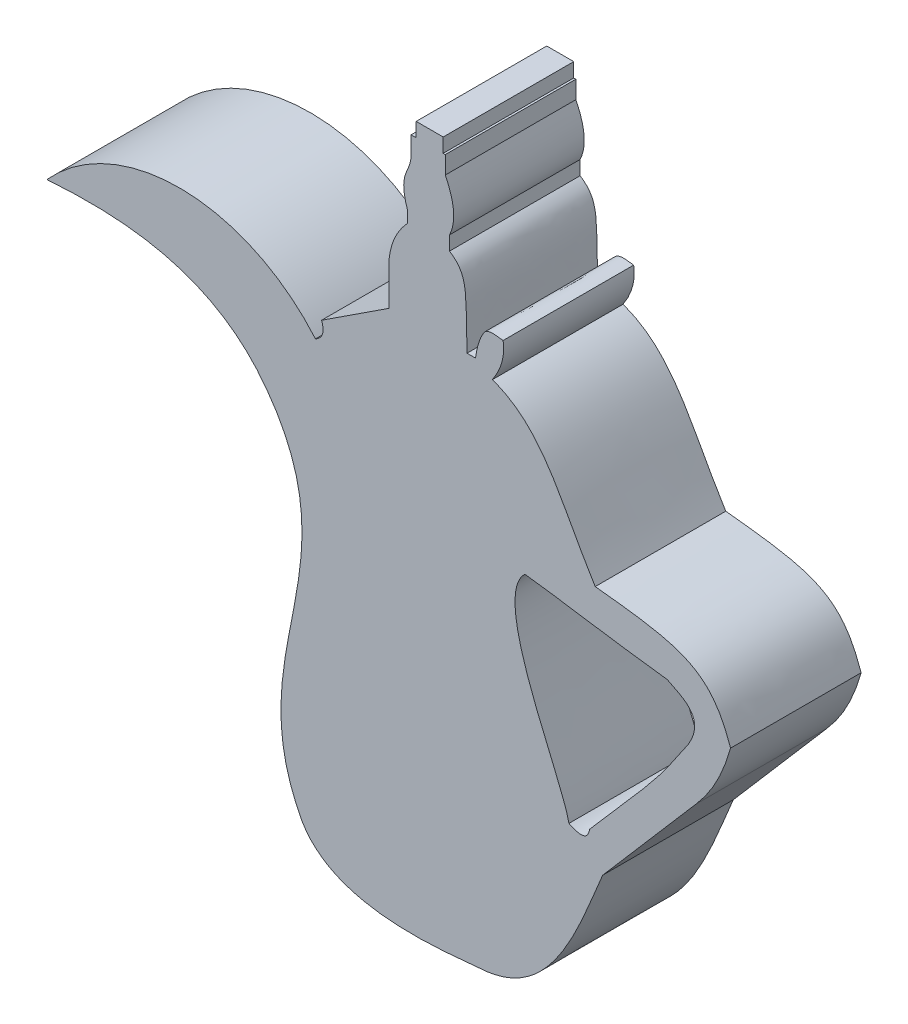
SolidWorks part; units mm, degrees
ref_plane "Front Plane" through (0, 0, 0) normal (0, 0, 1) x (1, 0, 0)
ref_plane "Top Plane" through (0, 0, 0) normal (0, 1, 0) x (1, 0, 0)
ref_plane "Right Plane" through (0, 0, 0) normal (1, 0, 0) x (0, 0, -1)
sketch "Sketch3" plane through (0, 0, 0) normal (0, 0, 1) x (1, 0, 0)
  line L0 (97.4864, 0) -> (97.4864, 192.0589) construction
  line L1 (104, 194) -> (111.2431, 194)
  line L8 (179, 73) -> (154, 44)
  line L9 (78.6407, 135.1556) -> (96.781, 147)
  line L11 (101.7339, 172.1213) -> (101.7339, 169.2571)
  line L12 (96.781, 154.2879) -> (96.781, 147)
  line L13 (112.9373, 172.1213) -> (112.9373, 168.3423)
  line L14 (117.6399, 147) -> (119.9041, 147)
  line L15 (102.6396, 185.6717) -> (102.6396, 190.1999)
  line L16 (102.6396, 190.1999) -> (104, 190.1999)
  line L17 (104, 190.1999) -> (104, 194)
  line L18 (111.2431, 194) -> (111.2431, 190.1999)
  line L19 (111.2431, 190.1999) -> (111.8092, 190.1999)
  line L20 (111.8092, 190.1999) -> (111.8092, 185.4453)
  arc A0 (5, 131) -> (77, 130) centre (40.5631, 99.0425) cw
  spline S0 degree 3 poles (152, 110) (175.0394, 107.5531) (182.9777, 106.0471) (188.2843, 90.6409) knots 0 0 0 0 1 1 1 1
  spline S1 degree 3 poles (154, 44) (147.8417, 29.6307) (140.82, 7.5363) (122, 6) (111.4509, 5.1389) (81.4356, 0.5974) (73, 17) (55.6312, 50.7726) (89.1322, 79.4015) (63, 113) (48.9787, 131.0274) (25.644, 132.4746) (5, 131) knots 0 0 0 0 1 1 1 2 2 2 3 3 3 4 4 4 4
  spline S2 degree 2 poles (77, 130) (79.9576, 131.6324) (78.6407, 135.1556) knots 0 0 0 1 1 1
  spline S3 degree 2 poles (101.7339, 169.2571) (95.8843, 162.9019) (96.781, 154.2879) knots 0 0 0 1 1 1
  spline S4 degree 3 poles (112.9373, 168.3423) (118.358, 164.8993) (117.1288, 160.2332) (117.6399, 147) knots 0 0 0 0 1 1 1 1
  spline S5 degree 2 poles (127.3064, 154.7913) (128.1025, 149.6964) (124.4326, 144.2539) knots 0 0 0 1 1 1
  spline S6 degree 3 poles (127.3064, 154.7913) (124.6311, 155.1584) (123.4032, 155.2462) (122.3425, 154.2879) knots 0 0 0 0 1 1 1 1
  spline S7 degree 2 poles (122.3425, 154.2879) (120.5691, 151.788) (119.9041, 147) knots 0 0 0 1 1 1
  spline S8 degree 3 poles (124.4326, 144.2539) (138.2527, 139.3739) (142.4846, 125.1118) (152, 110) knots 0 0 0 0 1 1 1 1
  spline S9 degree 3 poles (188.2843, 90.6409) (186.0331, 82.6368) (182.6956, 77.1591) (179, 73) knots 0 0 0 0 1 1 1 1
  spline S10 degree 3 poles (101.7339, 172.1213) (98.8559, 180.4243) (102.7038, 181.0801) (102.6396, 185.6717) knots 0 0 0 0 1 1 1 1
  spline S11 degree 2 poles (111.8092, 185.4453) (115.6307, 177.7386) (112.9373, 172.1213) knots 0 0 0 1 1 1
  spline S12 degree 3 poles (133.1582, 103.4337) (123.5257, 94.3516) (143.0393, 61.4582) (144.9538, 51.5026) knots 0 0 0 0 1 1 1 1
  spline S13 degree 3 poles (133.1582, 103.4337) (145.7949, 101.902) (150.5854, 100.6617) (171.3023, 98.0721) knots 0 0 0 0 1 1 1 1
  spline S14 degree 3 poles (171.3023, 98.0721) (175.2585, 95.9026) (183.2739, 93.7293) (175.132, 83.2127) knots 0 0 0 0 1 1 1 1
  spline S15 degree 3 poles (175.132, 83.2127) (168.0934, 72.6547) (166.3617, 71.2637) (150.4686, 52.8813) knots 0 0 0 0 1 1 1 1
  spline S16 degree 2 poles (144.9538, 51.5026) (149.9467, 49.0061) (150.4686, 52.8813) knots 0 0 0 1 1 1
extrude "Boss-Extrude1" add sketch "Sketch3" along normal blind 35
